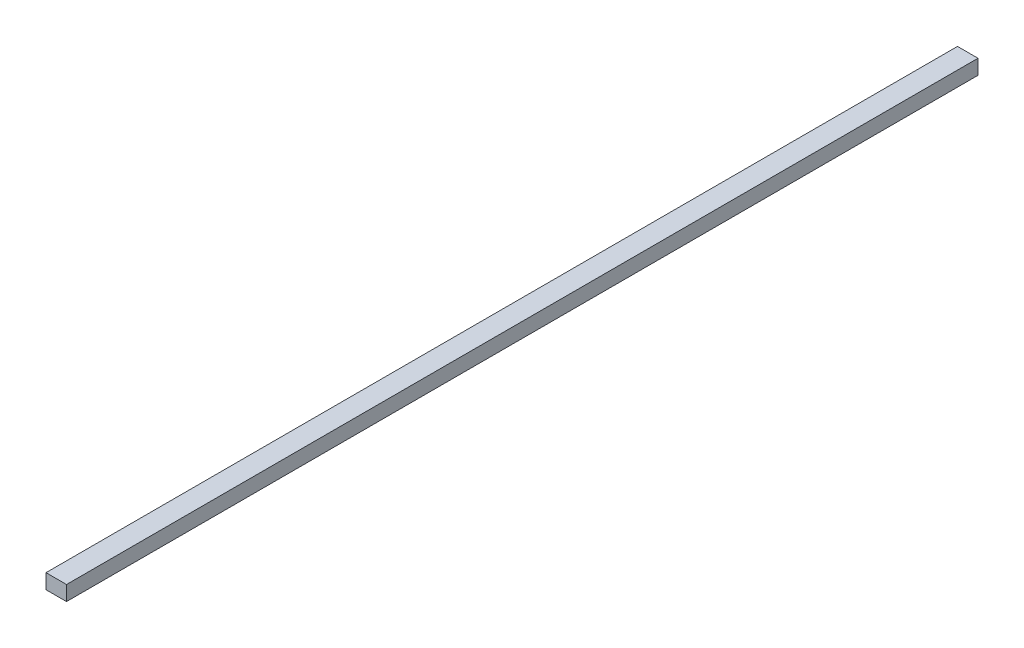
SolidWorks part; units mm, degrees
ref_plane "前视基准面" through (0, 0, 0) normal (0, 0, 1) x (1, 0, 0)
ref_plane "上视基准面" through (0, 0, 0) normal (0, 1, 0) x (1, 0, 0)
ref_plane "右视基准面" through (0, 0, 0) normal (1, 0, 0) x (0, 0, -1)
other "Configuration Table"
sketch "草图1" plane through (0, 0, 0) normal (0, 0, 1) x (1, 0, 0)
  line L1 (0, 0) -> (9, 0)
  line L2 (0, 0) -> (0, 6.5)
  line L3 (0, 6.5) -> (9, 6.5)
  line L4 (9, 0) -> (9, 6.5)
  dimension "D1" = 9
  dimension "D2" = 6.5
extrude "凸台-拉伸1" add sketch "草图1" along normal blind 400
